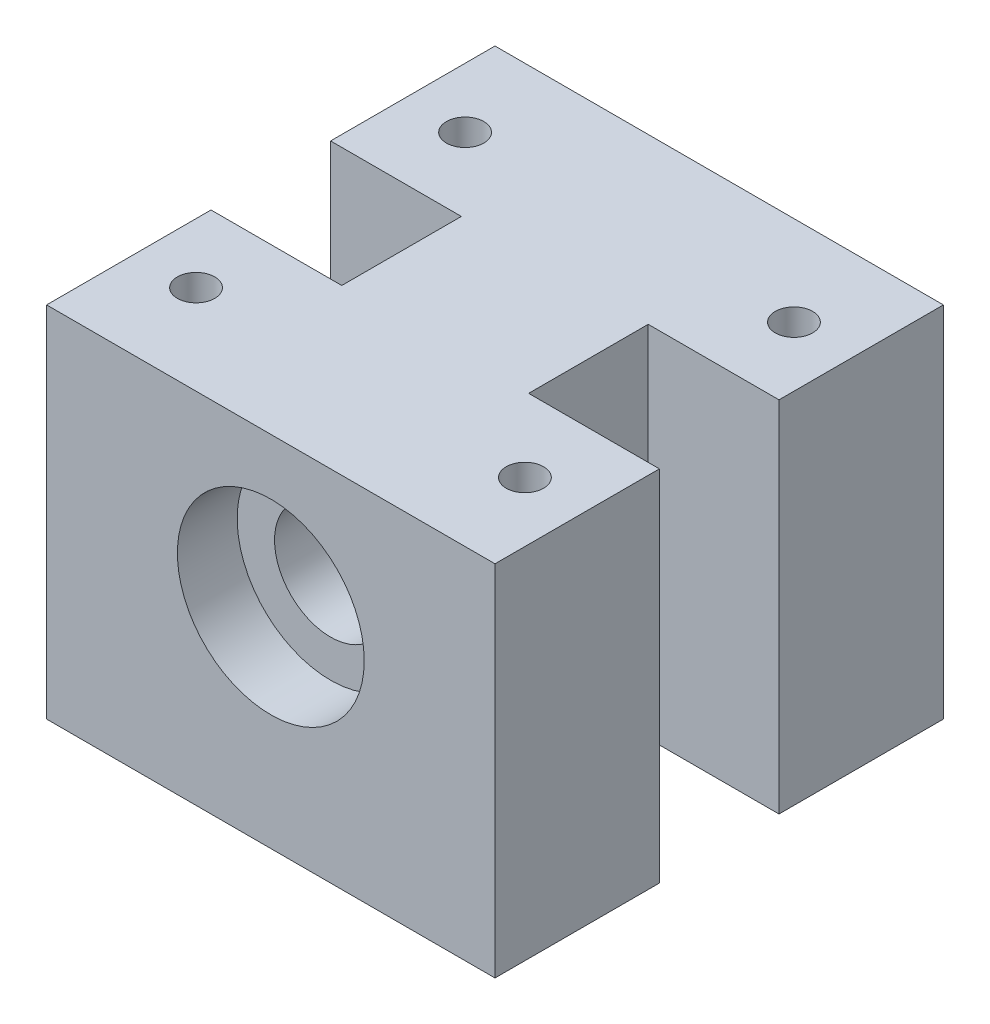
SolidWorks part; units mm, degrees
ref_plane "Front Plane" through (0, 0, 0) normal (0, 0, 1) x (1, 0, 0)
ref_plane "Top Plane" through (0, 0, 0) normal (0, 1, 0) x (1, 0, 0)
ref_plane "Right Plane" through (0, 0, 0) normal (1, 0, 0) x (0, 0, -1)
sketch "Sketch1" plane through (0, 0, 0) normal (0, 0, 1) x (1, 0, 0)
  line L1 (-19.05, -17.78) -> (19.05, -17.78)
  line L2 (-19.05, -17.78) -> (-19.05, 17.78)
  line L3 (-19.05, 17.78) -> (19.05, 17.78)
  line L4 (19.05, -17.78) -> (19.05, 17.78)
  line L5 (-19.05, -17.78) -> (19.05, 17.78) construction
  line L6 (-19.05, 17.78) -> (19.05, -17.78) construction
  point P0 (0, 0)
  dimension "D2" = 38.1
  dimension "D1" = 35.56
extrude "Boss-Extrude2" add sketch "Sketch1" along normal mid plane 38.1
sketch "Sketch2" plane through (0, 0, 19.05) normal (0, 0, 1) x (1, 0, 0)
  circle A0 centre (0, 0) radius 7.9375
  dimension "D1" = 15.875
extrude "Cut-Extrude1" cut sketch "Sketch2" against normal blind 5.08
sketch "Sketch3" plane through (0, 0, 13.97) normal (0, 0, 1) x (1, 0, 0)
  circle A0 centre (0, 0) radius 4.7625
  dimension "D1" = 9.525
extrude "Cut-Extrude2" cut sketch "Sketch3" against normal through all
mirror "Mirror1" about plane through (0, 0, 0) normal (0, 0, 1) of "Cut-Extrude1"
sketch "Sketch4" plane through (0, -17.78, 0) normal (0, -1, 0) x (1, 0, 0)
  line L0 (19.05, 19.05) -> (19.05, -19.05) construction
  line L1 (-13.97, 11.43) -> (13.97, 11.43)
  line L2 (-13.97, 11.43) -> (-13.97, -11.43)
  line L3 (-13.97, -11.43) -> (13.97, -11.43)
  line L4 (13.97, 11.43) -> (13.97, -11.43) construction
  line L5 (-13.97, 11.43) -> (13.97, -11.43) construction
  line L6 (-13.97, -11.43) -> (13.97, 11.43) construction
  line L7 (-19.05, -19.05) -> (19.05, -19.05) construction
  circle A0 centre (13.97, 11.43) radius 1.5875
  circle A1 centre (13.97, -11.43) radius 1.5875
  circle A2 centre (-13.97, -11.43) radius 1.5875
  circle A3 centre (-13.97, 11.43) radius 1.5875
  point P0 (0, 0)
  dimension "D1" = 5.08
  dimension "D2" = 7.62
extrude "Cut-Extrude3" cut sketch "Sketch4" against normal through all contours A0 | A1 | A2 | A3
sketch "Sketch5" plane through (0, 17.78, 0) normal (0, 1, 0) x (1, 0, 0)
  line L0 (19.05, -19.05) -> (19.05, 19.05) construction
  line L1 (19.05, 5.08) -> (7.9375, 5.08)
  line L2 (19.05, 5.08) -> (19.05, -5.08)
  line L3 (19.05, -5.08) -> (7.9375, -5.08)
  line L4 (7.9375, 5.08) -> (7.9375, -5.08)
  line L5 (4.7625, -13.97) -> (4.7625, 13.97) construction
  circle A0 centre (13.97, 11.43) radius 1.5875 construction
  circle A1 centre (13.97, -11.43) radius 1.5875 construction
  dimension "D2" = 6.35
  dimension "D1" = 3.175
  dimension "D3" = 6.35
extrude "Cut-Extrude4" cut sketch "Sketch5" against normal through all
mirror "Mirror2" about plane through (0, 0, 0) normal (1, 0, 0) of "Cut-Extrude4"
sketch "Sketch6" plane through (0, 17.78, 0) normal (0, 1, 0) x (1, 0, 0)
  line L12 (-19.05, 5.08) -> (-7.9375, 5.08)
  line L13 (-7.9375, 5.08) -> (-7.9375, -5.08)
  line L14 (-7.9375, -5.08) -> (-19.05, -5.08)
  line L15 (-19.05, -5.08) -> (-19.05, -19.05)
  line L16 (-19.05, -19.05) -> (19.05, -19.05)
  line L17 (19.05, -19.05) -> (19.05, -5.08)
  line L18 (19.05, -5.08) -> (7.9375, -5.08)
  line L19 (7.9375, -5.08) -> (7.9375, 5.08)
  line L20 (7.9375, 5.08) -> (19.05, 5.08)
  line L21 (19.05, 5.08) -> (19.05, 19.05)
  line L22 (19.05, 19.05) -> (-19.05, 19.05)
  line L23 (-19.05, 19.05) -> (-19.05, 5.08)
  line L24 (-19.05, 5.08) -> (-7.9375, 5.08)
  line L25 (-7.9375, 5.08) -> (-7.9375, -5.08)
  line L26 (-7.9375, -5.08) -> (-19.05, -5.08)
  line L27 (-19.05, -5.08) -> (-19.05, -19.05)
  line L28 (-19.05, -19.05) -> (19.05, -19.05)
  line L29 (19.05, -19.05) -> (19.05, -5.08)
  line L30 (19.05, -5.08) -> (7.9375, -5.08)
  line L31 (7.9375, -5.08) -> (7.9375, 5.08)
  line L32 (7.9375, 5.08) -> (19.05, 5.08)
  line L33 (19.05, 5.08) -> (19.05, 19.05)
  line L34 (19.05, 19.05) -> (-19.05, 19.05)
  line L35 (-19.05, 19.05) -> (-19.05, 5.08)
  dimension "D1" = 0
extrude "Cut-Extrude5" cut sketch "Sketch6" against normal blind 5.08
